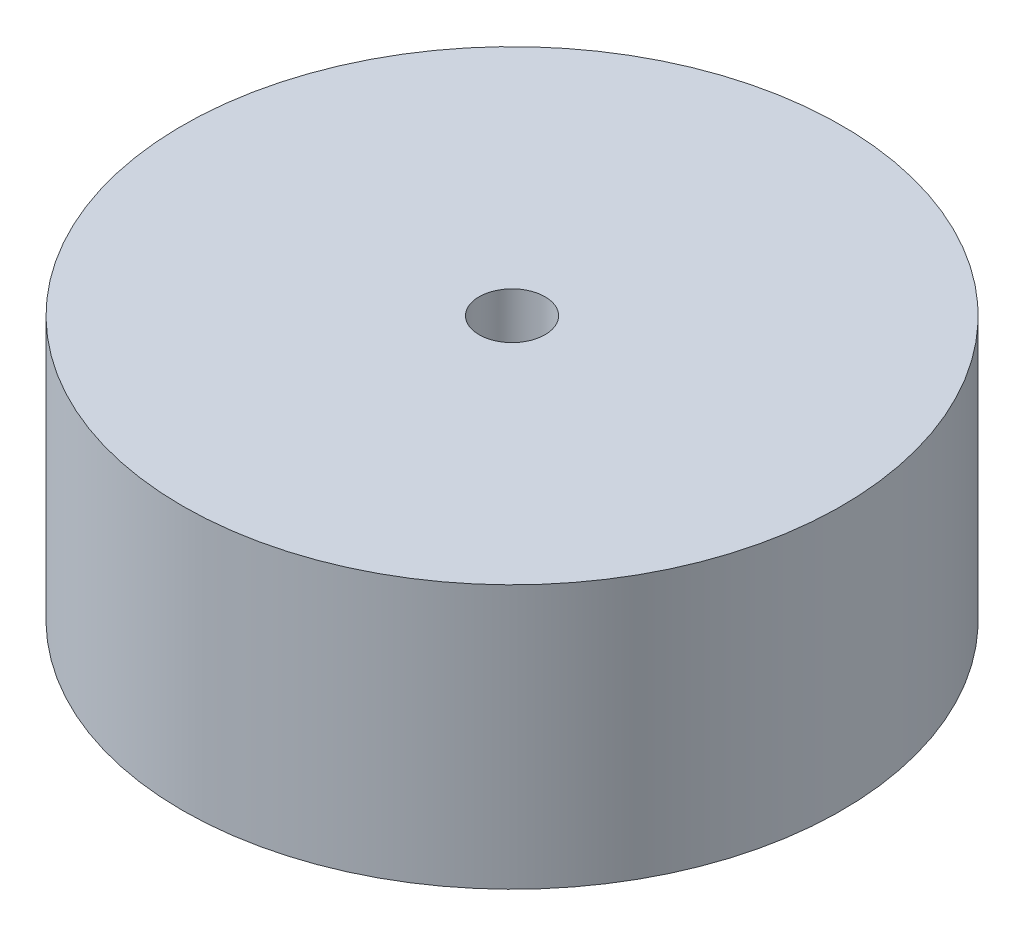
SolidWorks part; units mm, degrees
material "ABS"
ref_plane "前视基准面" through (0, 0, 0) normal (0, 0, 1) x (1, 0, 0)
ref_plane "上视基准面" through (0, 0, 0) normal (0, 1, 0) x (1, 0, 0)
ref_plane "右视基准面" through (0, 0, 0) normal (1, 0, 0) x (0, 0, -1)
sketch "Sketch1" plane through (0, 0, 0) normal (0, 1, 0) x (1, 0, 0)
  circle A0 centre (0, 0) radius 25
  circle A1 centre (0, 0) radius 2.5
  dimension "D1" = 50
  dimension "D2" = 5
extrude "Boss-Extrude1" add sketch "Sketch1" along normal blind 20
sketch "Sketch2" plane through (0, 0, 0) normal (0, -1, 0) x (1, 0, 0)
  arc A0 (-2, -3.4641) -> (-2, 3.4641) centre (0, 0) ccw
  arc A1 (-2, -1.5) -> (-2, 1.5) centre (0, 0) ccw
  arc A2 (-2, 3.4641) -> (-2, -3.4641) centre (0, 0) ccw
  arc A3 (-2, 1.5) -> (-2, -1.5) centre (0, 0) ccw
  dimension "D1" = 8
extrude "Boss-Extrude3" add sketch "Sketch2" along normal blind 14.5
sketch "Sketch7" plane through (0, 0, 0) normal (0, -1, 0) x (1, 0, 0)
  circle A0 centre (0, 0) radius 15
  dimension "D1" = 30
extrude "Boss-Extrude4" add sketch "Sketch7" along normal blind 3
fillet "Fillet1" radius 1 1 edges at (0, -3, -4)
